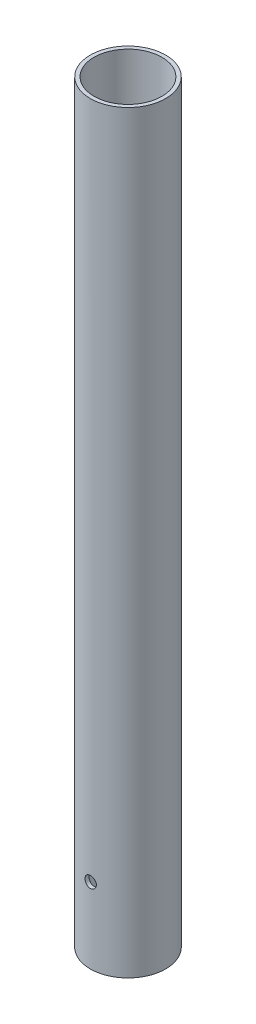
SolidWorks part; units mm, degrees
ref_plane "Front" through (0, 0, 0) normal (0, 0, 1) x (1, 0, 0)
ref_plane "Top" through (0, 0, 0) normal (0, 1, 0) x (1, 0, 0)
ref_plane "Right" through (0, 0, 0) normal (1, 0, 0) x (0, 0, -1)
sketch "草图1" plane through (0, 0, 0) normal (0, 1, 0) x (1, 0, 0)
  circle A0 centre (0, 0) radius 10
  circle A1 centre (0, 0) radius 9
  dimension "D1" = 20
  dimension "D2" = 18
extrude "凸台-拉伸1" add sketch "草图1" along normal blind 200
sketch "草图2" plane through (0, 0, 0) normal (0, 0, 1) x (1, 0, 0)
  line L0 (0, 0) -> (0, 200) construction
  line L1 (-10, 0) -> (10, 0) construction
  line L2 (9, 200) -> (-9, 200) construction
  circle A0 centre (0, 20) radius 1.5
  dimension "D1" = 3
  dimension "D2" = 20
extrude "切除-拉伸1" cut sketch "草图2" against normal through all both and the other way through all
